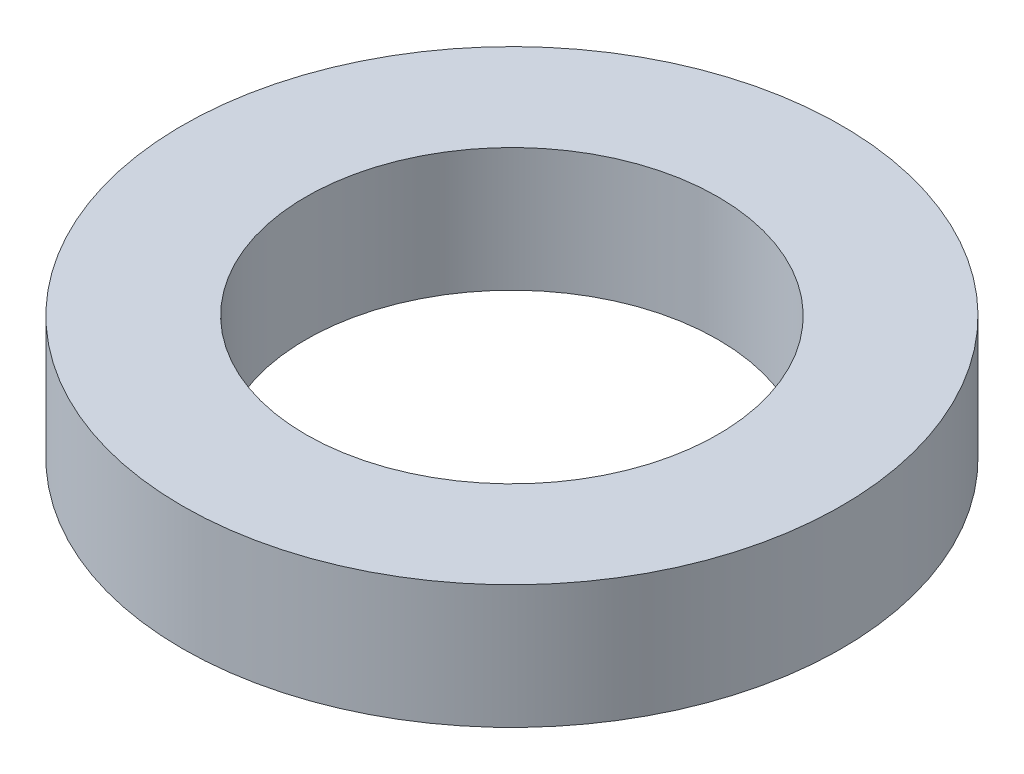
SolidWorks part; units mm, degrees
ref_plane "Front" through (0, 0, 0) normal (0, 0, 1) x (1, 0, 0)
ref_plane "Top" through (0, 0, 0) normal (0, 1, 0) x (1, 0, 0)
ref_plane "Right" through (0, 0, 0) normal (1, 0, 0) x (0, 0, -1)
sketch "Sketch1" plane through (0, 0, 0) normal (0, 1, 0) x (1, 0, 0)
  circle A0 centre (0, 0) radius 5
  circle A1 centre (0, 0) radius 8
  dimension "D1" = 10
  dimension "D2" = 3
extrude "Boss-Extrude1" add sketch "Sketch1" along normal blind 3
